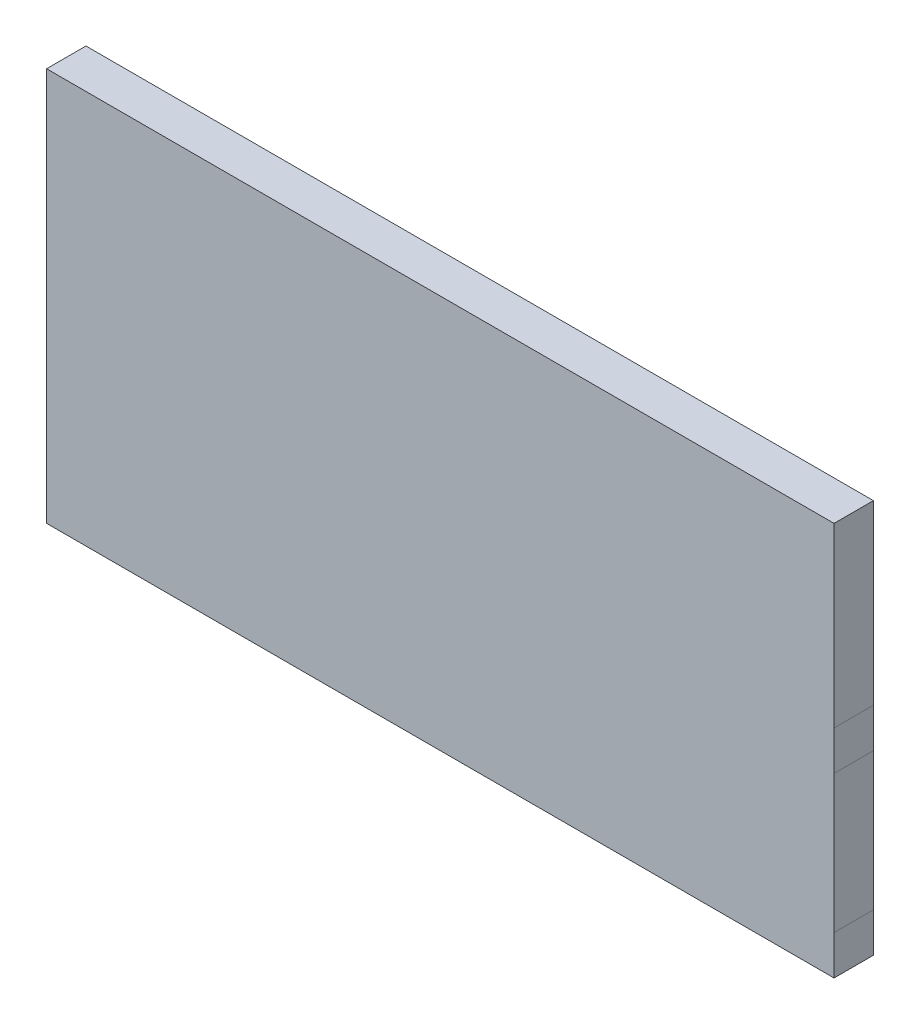
SolidWorks part; units mm, degrees
ref_plane "Front Plane" through (0, 0, 0) normal (0, 0, 1) x (1, 0, 0)
ref_plane "Top Plane" through (0, 0, 0) normal (0, 1, 0) x (1, 0, 0)
ref_plane "Right Plane" through (0, 0, 0) normal (1, 0, 0) x (0, 0, -1)
sketch "Sketch1" plane through (0, 0, 0) normal (0, 0, 1) x (1, 0, 0)
  line L1 (0, 0) -> (2000, 0)
  line L2 (0, 0) -> (0, 1000)
  line L3 (0, 1000) -> (2000, 1000)
  line L4 (2000, 0) -> (2000, 1000)
  dimension "D1" = 2000
  dimension "D2" = 1000
extrude "Boss-Extrude1" add sketch "Sketch1" along normal blind 100
sketch "Sketch2" plane through (2000, 0, 0) normal (1, 0, 0) x (0, 0, -1)
  line L0 (-100, 100) -> (0, 100)
  line L1 (-100, 0) -> (-100, 1000) construction
  line L2 (0, 0) -> (0, 1000) construction
  line L3 (-100, 450) -> (0, 450)
  line L4 (-100, 550) -> (0, 550)
  line L5 (-100, 0) -> (0, 0) construction
  dimension "D1" = 100
  dimension "D2" = 100
  dimension "D3" = 450
split line "Split Line1"
